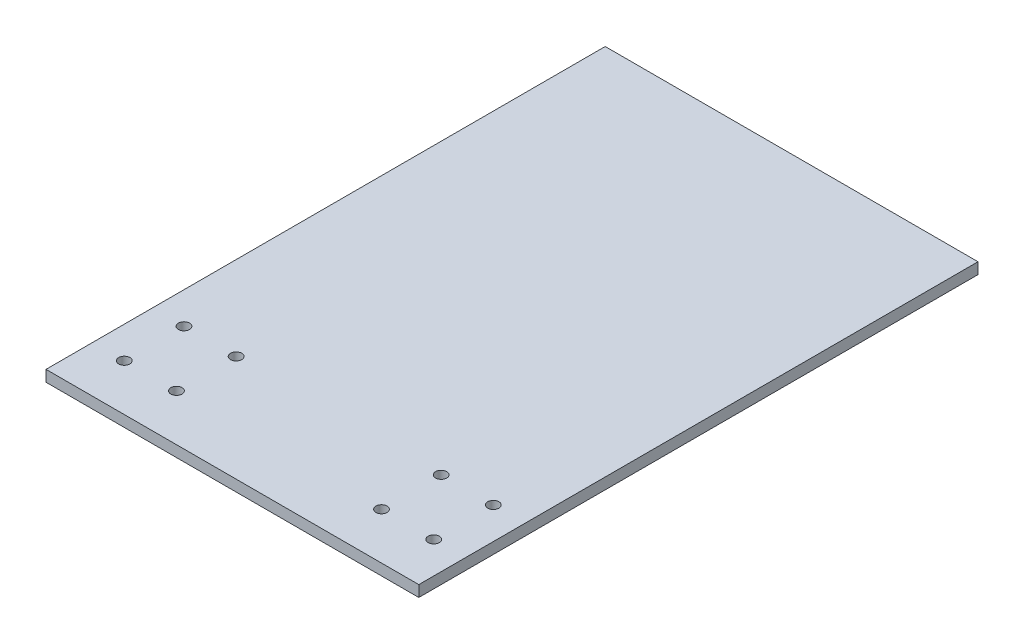
SolidWorks part; units mm, degrees
ref_plane "前视基准面" through (0, 0, 0) normal (0, 0, 1) x (1, 0, 0)
ref_plane "上视基准面" through (0, 0, 0) normal (0, 1, 0) x (1, 0, 0)
ref_plane "右视基准面" through (0, 0, 0) normal (1, 0, 0) x (0, 0, -1)
sketch "草图1" plane through (0, 0, 0) normal (0, 1, 0) x (1, 0, 0)
  line L0 (-40, -62.5) -> (-40, -55.0444) construction
  line L1 (-50, 75) -> (50, 75)
  line L2 (-50, 75) -> (-50, -75)
  line L3 (-50, -75) -> (50, -75)
  line L4 (50, 75) -> (50, -75)
  line L5 (-50, 75) -> (50, -75) construction
  line L6 (-50, -75) -> (50, 75) construction
  line L7 (-41.5, -61) -> (-45.5374, -61) construction
  line L8 (0, 75) -> (0, -135.6563) construction
  line L10 (-34.5, -36.7559) -> (-34.5, -74.1511) construction
  line L12 (-27.5, -54.5) -> (-68.8772, -54.5) construction
  circle A0 centre (-41.5, -62.5) radius 1.5
  circle A4 centre (-41.5, -46.5) radius 1.5
  circle A5 centre (-27.5, -62.5) radius 1.5
  circle A6 centre (-27.5, -46.5) radius 1.5
  circle A7 centre (41.5, -62.5) radius 1.5
  circle A8 centre (27.5, -62.5) radius 1.5
  circle A9 centre (27.5, -46.5) radius 1.5
  circle A10 centre (41.5, -46.5) radius 1.5
  point P0 (0, 0)
  dimension "D3" = 3
  dimension "D6" = 20.5
  dimension "D1" = 100
  dimension "D2" = 150
  dimension "D4" = 10
  dimension "D5" = 14
  dimension "D7" = 15.5
extrude "凸台-拉伸1" add sketch "草图1" along normal blind 3
